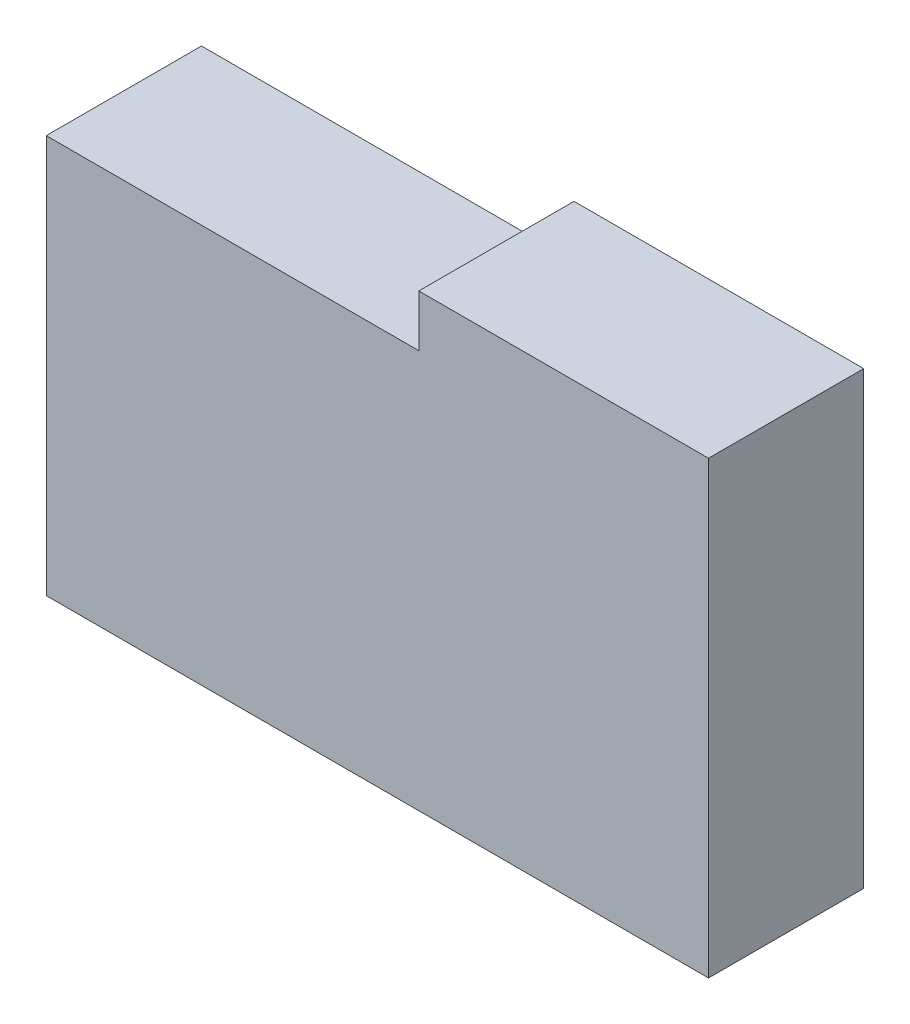
SolidWorks part; units mm, degrees
ref_plane "Plan de face" through (0, 0, 0) normal (0, 0, 1) x (1, 0, 0)
ref_plane "Plan de dessus" through (0, 0, 0) normal (0, 1, 0) x (1, 0, 0)
ref_plane "Plan de droite" through (0, 0, 0) normal (1, 0, 0) x (0, 0, -1)
sketch "Esquisse1" plane through (0, 0, 0) normal (0, 0, 1) x (1, 0, 0)
  line L0 (0, 0) -> (128, 0)
  line L1 (128, 0) -> (128, 87)
  line L2 (128, 87) -> (72, 87)
  line L3 (72, 87) -> (72, 77)
  line L4 (72, 77) -> (0, 77)
  line L5 (0, 77) -> (0, 0)
  line L7 (3, 74) -> (43, 74) construction
  line L8 (3, 74) -> (3, 3) construction
  line L9 (3, 3) -> (43, 3) construction
  line L10 (43, 74) -> (43, 3) construction
  line L11 (77.5, 64) -> (126.5, 64) construction
  line L12 (77.5, 64) -> (77.5, 6) construction
  line L13 (77.5, 6) -> (126.5, 6) construction
  line L14 (126.5, 64) -> (126.5, 6) construction
  dimension "D1" = 128
  dimension "D2" = 87
  dimension "D3" = 77
  dimension "D4" = 56
  dimension "D5" = 43
  dimension "D6" = 3
  dimension "D7" = 3
  dimension "D8" = 3
  dimension "D9" = 6
  dimension "D10" = 3
  dimension "D11" = 49
  dimension "D12" = 58
extrude "Boss.-Extru.1" add sketch "Esquisse1" against normal blind 30
sketch "Esquisse2" plane through (0, 0, 0) normal (0, 0, 1) x (1, 0, 0)
  text T0 "<b>Raspberry Pi 4</b>"
  text T1 "<b>DE0 Nano</b>\r\n\r\n"
